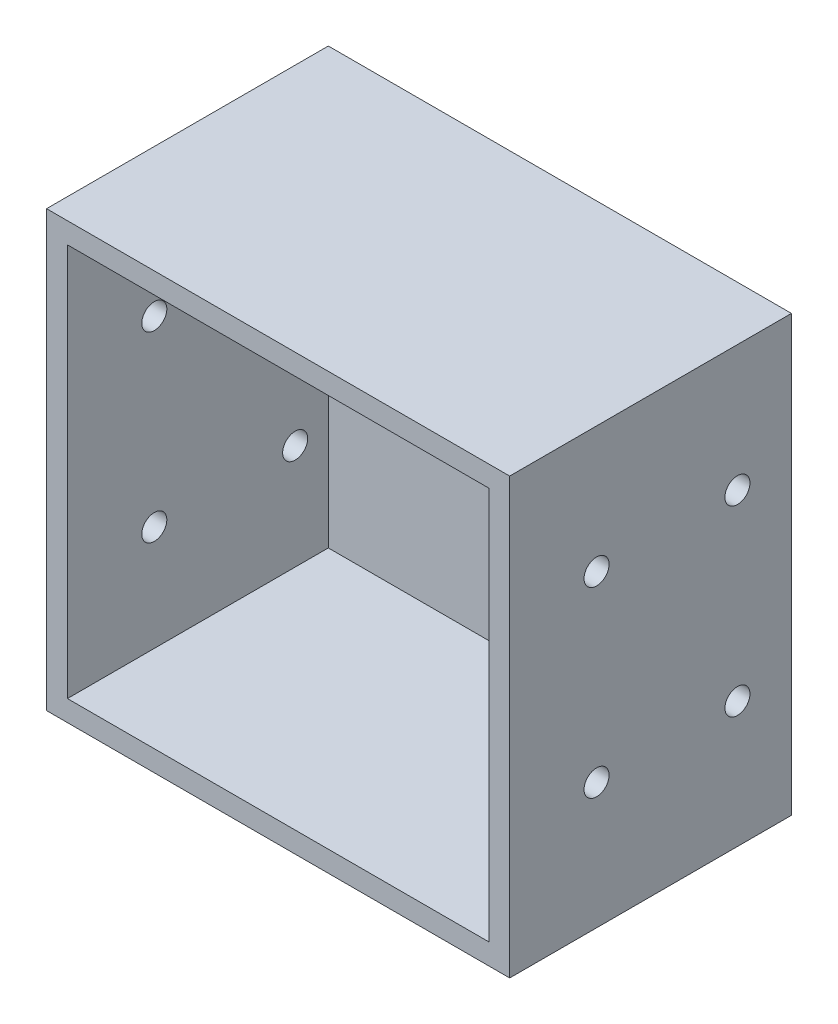
SolidWorks part; units mm, degrees
material "Custom Plastic"
ref_plane "X-Y Datum" through (0, 0, 0) normal (0, 0, 1) x (1, 0, 0)
ref_plane "X-Z Datum" through (0, 0, 0) normal (0, 1, 0) x (1, 0, 0)
ref_plane "Y-Z Datum" through (0, 0, 0) normal (1, 0, 0) x (0, 0, -1)
sketch "Sketch1" plane through (0, 0, 0) normal (0, 0, 1) x (1, 0, 0)
  line L0 (-40.381, 37.656) -> (40.381, 37.656)
  line L1 (-40, 37.275) -> (40, 37.275) construction
  line L2 (-40, 37.275) -> (-40, -37.275) construction
  line L3 (-40, -37.275) -> (40, -37.275) construction
  line L4 (40, 37.275) -> (40, -37.275) construction
  line L5 (-40, 37.275) -> (40, -37.275) construction
  line L6 (-40, -37.275) -> (40, 37.275) construction
  line L7 (40.381, 37.656) -> (40.381, -37.656)
  line L8 (-40.381, -37.656) -> (40.381, -37.656)
  line L9 (-40.381, 37.656) -> (-40.381, -37.656)
  point P0 (0, 0)
  dimension "D1" = 80
  dimension "D2" = 74.55
  dimension "D3" = 0.381
extrude "Boss-Extrude1" add sketch "Sketch1" along normal blind 50
shell "Shell1" thickness 4
sketch "Sketch2" plane through (44.381, 0, 0) normal (1, 0, 0) x (0, 0, -1)
  circle A0 centre (-33.35, 17.5) radius 3.025 construction
  circle A1 centre (-6.35, 17.5) radius 3.025 construction
  circle A2 centre (-6.35, -17.5) radius 3.025 construction
  circle A3 centre (-33.35, -17.5) radius 3.025 construction
  circle A4 centre (-33.35, 17.5) radius 3.025 construction
  circle A5 centre (-6.35, 17.5) radius 3.025 construction
  circle A6 centre (-6.35, -17.5) radius 3.025 construction
  circle A7 centre (-33.35, -17.5) radius 3.025 construction
hole_wizard "M4 Clearance Hole1" positions "Sketch3" profile "Sketch4" hole size "M4" standard "ANSI Metric" end condition through all
sketch "Sketch3" plane through (44.381, 0, 0) normal (1, 0, 0) x (0, 0, -1)
  point P0 (-33.35, -17.5)
  point P3 (-6.35, -17.5)
  point P6 (-33.35, 17.5)
  point P9 (-6.35, 17.5)
sketch "Sketch4" plane through (44.381, -17.5, 33.35) normal (0, 1, 0) x (0, 0, -1)
  line L0 (0, 0) -> (0, 88.762)
  line L1 (0, 88.762) -> (2.4, 88.762)
  line L2 (2.4, 88.762) -> (2.4, 0)
  line L5 (2.4, 0) -> (0, 0)
  line L11 (0, -6.35) -> (0, 107.95) construction
  dimension "Thru Hole Dia." = 4.8
  dimension "Thru Hole Depth" = 88.762
